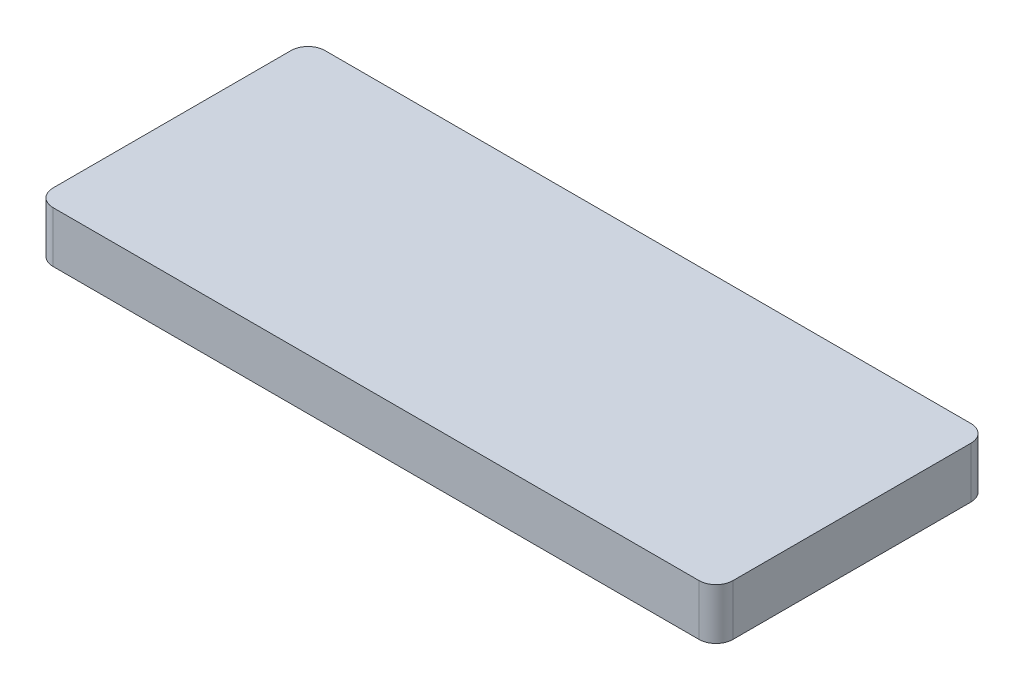
SolidWorks part; units mm, degrees
ref_plane "Front Plane" through (0, 0, 0) normal (0, 0, 1) x (1, 0, 0)
ref_plane "Top Plane" through (0, 0, 0) normal (0, 1, 0) x (1, 0, 0)
ref_plane "Right Plane" through (0, 0, 0) normal (1, 0, 0) x (0, 0, -1)
sketch "Sketch1" plane through (0, 0, 0) normal (0, 1, 0) x (1, 0, 0)
  line L1 (-100, -40) -> (100, -40)
  line L2 (-100, -40) -> (-100, 40)
  line L3 (-100, 40) -> (100, 40)
  line L4 (100, -40) -> (100, 40)
  line L5 (-100, -40) -> (100, 40) construction
  line L6 (-100, 40) -> (100, -40) construction
  point P0 (0, 0)
  dimension "D1" = 200
  dimension "D2" = 80
extrude "Boss-Extrude1" add sketch "Sketch1" along normal mid plane 15
fillet "Fillet1" radius 5 4 edges at (100, 0, 40) (100, 0, -40) (-100, 0, -40) (-100, 0, 40)
